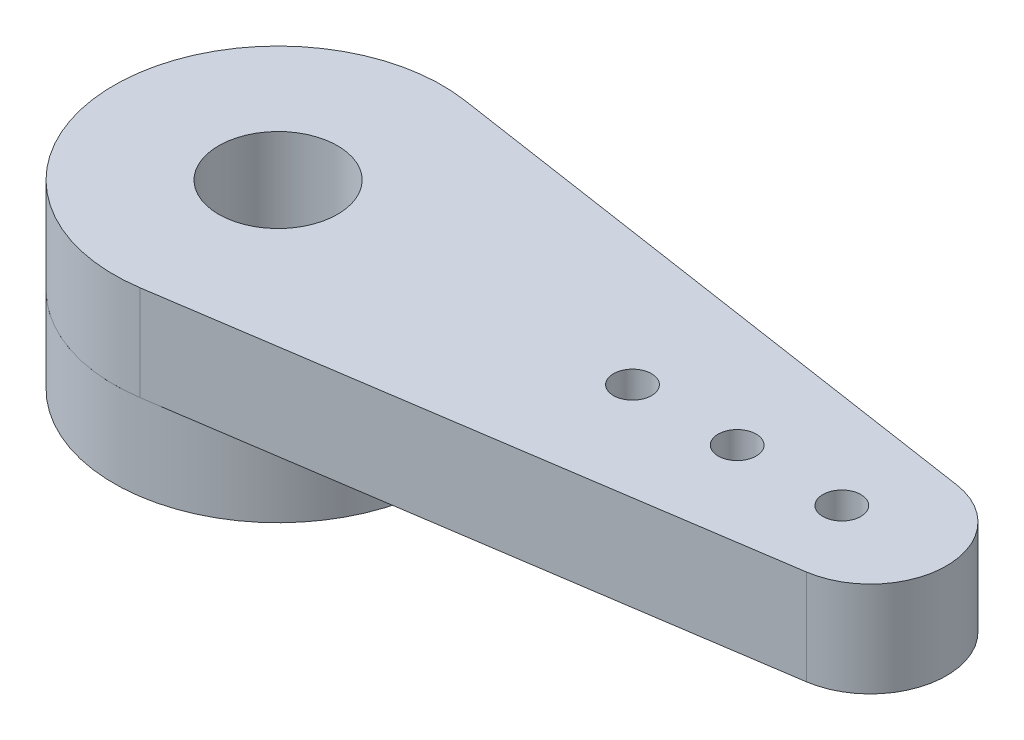
SolidWorks part; units mm, degrees
ref_plane "Front Plane" through (0, 0, 0) normal (0, 0, 1) x (1, 0, 0)
ref_plane "Top Plane" through (0, 0, 0) normal (0, 1, 0) x (1, 0, 0)
ref_plane "Right Plane" through (0, 0, 0) normal (1, 0, 0) x (0, 0, -1)
sketch "Sketch1" plane through (0, 0, 0) normal (0, 1, 0) x (1, 0, 0)
  line L0 (0, 0) -> (113.3194, 0) construction
  line L1 (0.5127, 3.4117) -> (12.6878, 1.5822)
  line L2 (0.5127, -3.4117) -> (12.6878, -1.5822)
  arc A0 (0.5127, -3.4117) -> (0.5127, 3.4117) centre (0, 0) cw
  arc A1 (12.6878, 1.5822) -> (12.6878, -1.5822) centre (12.45, 0) cw
  circle A2 centre (7.45, 0) radius 0.4
  circle A3 centre (9.65, 0) radius 0.4
  circle A4 centre (11.85, 0) radius 0.4
  circle A5 centre (0, 0) radius 1.25
  dimension "D1" = 3.45
  dimension "D3" = 1.6
  dimension "D2" = 0.8
  dimension "D4" = 0.8
  dimension "D5" = 0.8
  dimension "D7" = 2.5
  dimension "D6" = 2.2
  dimension "D8" = 2.2
extrude "Boss-Extrude1" add sketch "Sketch1" along normal blind 2
sketch "Sketch2" plane through (0, 0, 0) normal (0, -1, 0) x (1, 0, 0)
  circle A0 centre (0, 0) radius 3.45
  circle A1 centre (0, 0) radius 2.25
  arc A2 (0.5127, 3.4117) -> (0.5127, -3.4117) centre (0, 0) ccw construction
  dimension "D1" = 4.5
extrude "Boss-Extrude2" add sketch "Sketch2" along normal blind 1.8 separate body
